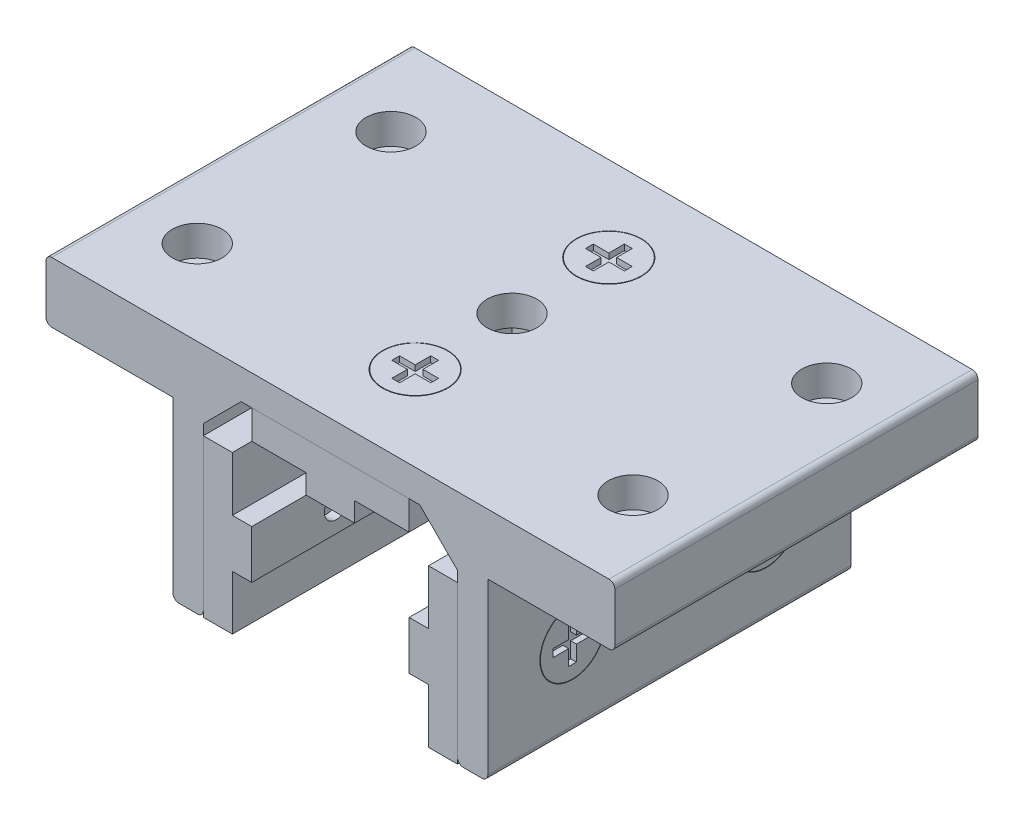
SolidWorks part; units mm, degrees
ref_plane "Front Plane" through (0, 0, 0) normal (0, 0, 1) x (1, 0, 0)
ref_plane "Top Plane" through (0, 0, 0) normal (0, 1, 0) x (1, 0, 0)
ref_plane "Right Plane" through (0, 0, 0) normal (1, 0, 0) x (0, 0, -1)
sketch "Sketch1" plane through (0, 0, 0) normal (0, 0, 1) x (1, 0, 0)
  line L0 (0, -15.4686) -> (0, 15.4686) construction
  line L1 (-20.6375, 0) -> (20.6375, 0) construction
  line L3 (-20.6375, -15.475) -> (-16.6687, -15.475) construction
  line L4 (-16.6687, -15.475) -> (-16.6687, 6.5389) construction
  line L5 (-16.6687, 6.5389) -> (-11.7078, 11.4998) construction
  line L6 (-11.7078, 11.4998) -> (11.7078, 11.4998) construction
  line L7 (11.7078, 11.4998) -> (16.6687, 6.5389) construction
  line L8 (16.6687, 6.5389) -> (16.6688, -15.4749) construction
  line L9 (16.6688, -15.4749) -> (20.6375, -15.475) construction
  line L10 (20.6375, -15.475) -> (20.6375, 7.5311) construction
  line L11 (20.6375, 7.5311) -> (-20.6375, 7.5311) construction
  line L14 (-16.6687, 5.1498) -> (-12.8588, 5.1498) construction
  line L15 (-12.8588, 5.1498) -> (-12.8587, -1.9876) construction
  line L16 (-12.8587, -1.9876) -> (-10.3187, -1.9876) construction
  line L17 (-10.3187, -1.9876) -> (-10.3187, -8.3376) construction
  line L18 (-10.3187, -8.3376) -> (-12.8587, -8.3376) construction
  line L19 (-12.8587, -8.3376) -> (-12.8587, -15.475) construction
  line L20 (-12.8587, -15.475) -> (-16.6687, -15.475) construction
  line L21 (-12.8587, -1.9876) -> (-12.8587, -8.3376) construction
  line L22 (-10.3187, -5.1626) -> (-16.6687, -5.1626) construction
  line L23 (-16.6687, -5.1626) -> (20.6375, -5.1626) construction
  line L24 (-37.2999, 15.4686) -> (37.2999, 15.4686) construction
  line L25 (-37.2999, 15.4686) -> (-37.2999, 7.5311) construction
  line L26 (-37.2999, 7.5311) -> (-20.6375, 7.5311) construction
  line L27 (-20.6375, 7.5311) -> (-20.6375, -15.475) construction
  line L28 (37.2999, 15.4686) -> (37.2999, 7.5311) construction
  line L29 (37.2999, 7.5311) -> (20.6375, 7.5311) construction
  point P4 (0, 0)
  point P7 (0, 0)
  point P30 (0, 11.4998)
  point P31 (0, 4.3561)
  dimension "Length (B)" = 30.9372
  dimension "Length1" = 41.275
  dimension "D1" = 3.9688
  dimension "Chamfer" = 4.9609
  dimension "D2" = 45
  dimension "Pad Width" = 20.6248
  dimension "Pad Height" = 6.35
  dimension "Pad Thickness" = 3.81
  dimension "Pad Rail" = 6.35
  dimension "Countersink Depth" = 3.175
  dimension "Inner Height" = 26.9748
  dimension "Length (A)" = 74.5998
  dimension "Mounting Hole Depth" = 7.9375
  dimension "D4" = 3.9688
sketch "Sketch2" plane through (0, 0, 0) normal (1, 0, 0) x (0, 0, -1)
  line L0 (-23.8125, 0) -> (23.8125, 0) construction
  line L1 (-23.8125, 7.5311) -> (23.8125, 7.5311) construction
  line L2 (-23.8125, 15.4686) -> (23.8125, 15.4686) construction
  line L3 (-23.8125, 15.4686) -> (-23.8125, -15.4686) construction
  line L4 (-23.8125, -15.4686) -> (23.8125, -15.4686) construction
  line L5 (23.8125, 15.4686) -> (23.8125, -15.4686) construction
  line L7 (0, 15.4686) -> (0, 7.5311) construction
  line L8 (-12.7, 11.4999) -> (12.7, 11.4999) construction
  line L9 (-23.8125, -5.1626) -> (23.8125, -5.1625) construction
  line L10 (-13.2105, -7.7153) -> (-12.1895, -7.7153) construction
  line L11 (-13.2105, -7.7153) -> (-13.2105, -2.6099) construction
  line L12 (-13.2105, -2.6099) -> (-12.1895, -2.6099) construction
  line L13 (-12.1895, -7.7153) -> (-12.1895, -2.6099) construction
  line L14 (-12.7, -2.6098) -> (-12.7, -7.7153) construction
  line L15 (-13.2105, -5.1626) -> (-12.1895, -5.1626) construction
  line L16 (-15.2527, -4.652) -> (-10.1473, -4.652) construction
  line L17 (-15.2527, -4.652) -> (-15.2527, -5.6731) construction
  line L18 (-15.2527, -5.6731) -> (-10.1473, -5.6731) construction
  line L19 (-10.1473, -4.652) -> (-10.1473, -5.6731) construction
  line L20 (-12.7, -5.6731) -> (-12.7, -4.652) construction
  line L21 (-15.2527, -5.1626) -> (-10.1473, -5.1626) construction
  line L22 (12.7, -2.6098) -> (-12.7, -2.6098) construction
  line L23 (0, -5.1626) -> (0, -2.6098) construction
  circle A0 centre (-12.7, 11.4999) radius 3.2639 construction
  circle A1 centre (12.7, 11.4999) radius 3.2639 construction
  circle A2 centre (0, -5.1626) radius 3.2639 construction
  circle A3 centre (-12.7, -5.1626) radius 2.5527 construction
  circle A4 centre (12.7, -5.1626) radius 2.5527 construction
  circle A5 centre (12.7, -5.1626) radius 1.5875
  circle A6 centre (-12.7, -5.1626) radius 1.5875
  point P12 (0, 7.5311)
  point P19 (0, 11.4998)
  point P22 (0, -5.1626)
  point P42 (0, -5.1626)
  dimension "Mounting Hole Diameter" = 6.5278
  dimension "Hole Diameter 2" = 6.5278
  dimension "D1" = 5.1054
  dimension "Pilot Hole" = 3.175
  dimension "Length" = 47.625
  dimension "Mounting Hole Spacing" = 25.4
  dimension "D2" = 1.0211
sketch "Sketch3" plane through (0, 0, 0) normal (0, 1, 0) x (1, 0, 0)
  line L0 (0, -23.8125) -> (0, 23.8125) construction
  line L1 (0, 12.7) -> (0, -12.7) construction
  line L5 (0, -23.8125) -> (0, 23.8125) construction
  line L7 (-28.575, 12.7) -> (28.575, 12.7) construction
  line L8 (-28.575, 12.7) -> (-28.575, -12.7) construction
  circle A0 centre (0, 12.7) radius 2.5527 construction
  circle A1 centre (0, -12.7) radius 2.5527 construction
  circle A2 centre (0, 0) radius 3.2639 construction
  circle A3 centre (0, 12.7) radius 4.2164 construction
  circle A4 centre (0, -12.7) radius 4.2164 construction
  circle A5 centre (-28.575, 12.7) radius 3.2639 construction
  circle A6 centre (28.575, 12.7) radius 3.2639 construction
  circle A7 centre (28.575, -12.7) radius 3.2639 construction
  circle A8 centre (-28.575, -12.7) radius 3.2639 construction
  dimension "D1" = 6.5278
  dimension "D2" = 5.1054
  dimension "Countersink Diameter" = 8.4328
  dimension "Hole Spacing2" = 57.15
ref_plane "Plane1" through (0, 0, 12.7) normal (0, 0, 1) x (1, 0, 0)
sketch "Sketch11" plane through (0, 0, 12.7) normal (0, 0, 1) x (1, 0, 0)
  line L0 (-16.6687, -5.1626) -> (-20.6375, -5.1626) construction
  line L2 (-20.6375, -0.9462) -> (-20.6375, -9.379) construction
  line L3 (-20.6375, -0.9462) -> (-19.1243, -2.7496) construction
  line L4 (-19.1243, -2.7496) -> (-19.1243, -7.5756) construction
  line L5 (-19.1243, -7.5756) -> (-20.6375, -9.379) construction
  line L6 (-19.1243, -2.7496) -> (-11.5887, -2.7496) construction
  line L7 (-11.5887, -2.7496) -> (-11.5887, -1.9876) construction
  line L8 (-12.8587, -1.9876) -> (-10.3187, -1.9876) construction
  line L9 (-20.6375, 7.5311) -> (-20.6375, -15.475) construction
  point P7 (-19.8809, -1.8479)
  dimension "D1" = 8.4328
  dimension "D2" = 100
  dimension "D3" = 4.826
sketch "Sketch4" plane through (0, 0, 0) normal (0, 0, 1) x (1, 0, 0)
  line L0 (-20.6375, -15.475) -> (-16.6687, -15.475) construction
  line L5 (20.6375, -15.475) -> (20.6375, 7.5311) construction
  line L6 (16.6688, -15.4749) -> (20.6375, -15.475) construction
  line L7 (16.6687, 6.5389) -> (16.6688, -15.4749) construction
  line L8 (11.7078, 11.4998) -> (16.6687, 6.5389) construction
  line L9 (-11.7078, 11.4998) -> (11.7078, 11.4998) construction
  line L10 (-16.6687, 6.5389) -> (-11.7078, 11.4998) construction
  line L11 (-16.6687, -15.475) -> (-16.6687, 6.5389) construction
  line L12 (-20.6375, -15.475) -> (-16.6687, -15.475)
  line L17 (20.6375, -15.475) -> (20.6375, 7.5311)
  line L18 (16.6688, -15.4749) -> (20.6375, -15.475)
  line L19 (16.6687, 6.5389) -> (16.6688, -15.4749)
  line L20 (11.7078, 11.4998) -> (16.6687, 6.5389)
  line L21 (-11.7078, 11.4998) -> (11.7078, 11.4998)
  line L22 (-16.6687, 6.5389) -> (-11.7078, 11.4998)
  line L23 (-16.6687, -15.475) -> (-16.6687, 6.5389)
  line L24 (-20.6375, -15.475) -> (-20.6375, 7.5311)
  line L25 (-20.6375, 7.5311) -> (-37.2999, 7.5311)
  line L26 (-37.2999, 7.5311) -> (-37.2999, 15.4686)
  line L27 (-37.2999, 15.4686) -> (37.2999, 15.4686)
  line L28 (37.2999, 15.4686) -> (37.2999, 7.5311)
  line L29 (37.2999, 7.5311) -> (20.6375, 7.5311)
extrude "Boss-Extrude1" add sketch "Sketch4" along normal up to vertex (23.8125 mm away) and the other way up to vertex (23.8125 mm away) up to point (0, -15.4686, 23.8125) other way up to point (0, 0, -23.8125)
sketch "Sketch5" plane through (0, 0, 0) normal (0, 0, 1) x (1, 0, 0)
  line L0 (-16.6687, 5.1498) -> (-16.6687, -15.475)
  line L1 (-16.6687, -15.475) -> (-12.8587, -15.475)
  line L2 (-12.8587, -15.475) -> (-12.8587, -8.3376)
  line L3 (-12.8587, -8.3376) -> (-10.3187, -8.3376)
  line L4 (-10.3187, -8.3376) -> (-10.3187, -1.9876)
  line L5 (-10.3187, -1.9876) -> (-12.8587, -1.9876)
  line L6 (-12.8587, -1.9876) -> (-12.8588, 5.1498)
  line L7 (-12.8588, 5.1498) -> (-16.6687, 5.1498)
extrude "Boss-Extrude2" add sketch "Sketch5" along normal up to surface and the other way up to surface from offset 1.7272 separate body
sketch "Sketch6" plane through (0, 0, 0) normal (1, 0, 0) x (0, 0, -1)
  circle A0 centre (-12.7, -5.1626) radius 2.5527 construction
  circle A1 centre (0, -5.1626) radius 3.2639 construction
  circle A2 centre (12.7, -5.1626) radius 2.5527 construction
  circle A5 centre (-12.7, -5.1626) radius 2.5527
  circle A6 centre (0, -5.1626) radius 3.2639
  circle A7 centre (12.7, -5.1626) radius 2.5527
extrude "Cut-Extrude1" cut sketch "Sketch6" against normal through all both and the other way through all
sketch "Sketch7" plane through (0, 0, 0) normal (1, 0, 0) x (0, 0, -1)
  line L1 (-3.2639, -8.4265) -> (3.2639, -8.4265)
  line L2 (-3.2639, -8.4265) -> (-3.2639, -1.8986)
  line L3 (-3.2639, -1.8986) -> (3.2639, -1.8986)
  line L4 (3.2639, -8.4265) -> (3.2639, -1.8986)
  line L5 (0, -1.8986) -> (0, -8.4265) construction
  line L6 (-3.2639, -5.1626) -> (3.2639, -5.1626) construction
  circle A0 centre (-12.7, -5.1626) radius 1.5875 construction
  circle A1 centre (-12.7, -5.1626) radius 1.5875
  circle A2 centre (12.7, -5.1626) radius 1.5875 construction
  circle A3 centre (12.7, -5.1626) radius 1.5875
  circle A4 centre (0, -5.1626) radius 3.2639 construction
  point P6 (0, -5.1626)
extrude "Cut-Extrude2" cut sketch "Sketch7" against normal through all
sketch "Sketch8" plane through (0, 15.4686, 0) normal (0, 1, 0) x (1, 0, 0)
  circle A0 centre (0, 12.7) radius 2.5527 construction
  circle A1 centre (0, -12.7) radius 2.5527 construction
  circle A2 centre (0, 12.7) radius 2.5527
  circle A3 centre (0, -12.7) radius 2.5527
  circle A4 centre (28.575, -12.7) radius 3.2639 construction
  circle A5 centre (28.575, 12.7) radius 3.2639 construction
  circle A6 centre (0, 0) radius 3.2639 construction
  circle A7 centre (-28.575, -12.7) radius 3.2639 construction
  circle A8 centre (-28.575, 12.7) radius 3.2639 construction
  circle A9 centre (28.575, -12.7) radius 3.2639
  circle A10 centre (28.575, 12.7) radius 3.2639
  circle A11 centre (0, 0) radius 3.2639
  circle A12 centre (-28.575, -12.7) radius 3.2639
  circle A13 centre (-28.575, 12.7) radius 3.2639
extrude "Cut-Extrude3" cut sketch "Sketch8" against normal up to vertex (3.9688 mm away) up to point (0, 11.4998, 0)
chamfer "Chamfer1" distance 1.7272 angle 45 6 edges at (20.6375, -7.7153, 12.7) (20.6375, -7.7153, -12.7) (0, 15.4686, 15.2527) (0, 15.4686, -10.1473) (-20.6375, -2.6098, -12.7) (-20.6375, -2.6098, 12.7)
sketch "Sketch12" plane through (0, 0, 12.7) normal (0, 0, 1) x (1, 0, 0)
  line L0 (-20.6375, -0.9462) -> (-20.6375, -5.1626)
  line L1 (-20.6375, -5.1626) -> (-11.5887, -5.1626)
  line L2 (-11.5887, -5.1626) -> (-11.5887, -2.7496)
  line L3 (-11.5887, -2.7496) -> (-19.1243, -2.7496)
  line L4 (-19.1243, -2.7496) -> (-20.6375, -0.9462)
revolve "Revolve1" add sketch "Sketch12" angle 360 about L1
sketch "Sketch13" plane through (-20.6375, 0, 0) normal (-1, 0, 0) x (0, 0, 1)
  line L0 (13.2105, -7.7153) -> (12.1895, -7.7153) construction
  line L1 (13.2105, -7.7153) -> (13.2105, -2.6099) construction
  line L2 (13.2105, -2.6099) -> (12.1895, -2.6099) construction
  line L3 (12.1895, -7.7153) -> (12.1895, -2.6099) construction
  line L4 (13.2105, -7.7153) -> (12.1895, -7.7153)
  line L5 (13.2105, -7.7153) -> (13.2105, -5.6731)
  line L6 (13.2105, -2.6099) -> (12.1895, -2.6099)
  line L7 (12.1895, -7.7153) -> (12.1895, -5.6731)
  line L8 (15.2527, -4.652) -> (15.2527, -5.6731) construction
  line L9 (15.2527, -5.6731) -> (10.1473, -5.6731) construction
  line L10 (10.1473, -4.652) -> (10.1473, -5.6731) construction
  line L11 (15.2527, -4.652) -> (10.1473, -4.652) construction
  line L12 (15.2527, -4.652) -> (15.2527, -5.6731)
  line L13 (15.2527, -5.6731) -> (13.2105, -5.6731)
  line L14 (10.1473, -4.652) -> (10.1473, -5.6731)
  line L15 (15.2527, -4.652) -> (13.2105, -4.652)
  line L16 (12.1895, -4.652) -> (10.1473, -4.652)
  line L17 (12.1895, -4.652) -> (12.1895, -2.6099)
  line L18 (12.1895, -5.6731) -> (10.1473, -5.6731)
  line L19 (13.2105, -4.652) -> (13.2105, -2.6099)
extrude "Cut-Extrude5" cut sketch "Sketch13" against normal up to vertex (0.7566 mm away) up to point (-19.8809, -1.8479, 12.7)
pattern_linear "LPattern1" count 2 spacing 25.4 along (0, 0, -1) of bodies 111
pattern_circular "CirPattern1" count 3 over 180 about axis through (0, -5.1626, 0) along (0, 0, 1) of bodies 107 111 112
fillet "Fillet1" radius 0.762 8 edges at (20.6375, -15.475, 0) (16.6688, -15.4749, 0) (-16.6687, -15.475, 0) (37.2999, 7.5311, 0) (37.2999, 15.4686, 0) (-37.2999, 15.4686, 0) (-37.2999, 7.5311, 0) (-20.6375, -15.475, 0)
equation "\"D1@Sketch1\" = \"Mounting Hole Depth@Sketch1\" / 2"
equation "\"D1@Sketch3\"=\"Hole Diameter 2@Sketch2\""
equation "\"D2@Sketch3\"=\"D1@Sketch2\""
equation "\"D2@Sketch2\"=\"D1@Sketch2\"*.2"
equation "\"D1@Sketch11\"=\"Countersink Diameter@Sketch3\""
equation "\"D3@LPattern1\"=\"Mounting Hole Spacing@Sketch2\""
equation "\"Chamfer@Sketch1\"=\"Mounting Hole Depth@Sketch1\"*.625"
equation "\"D4@Sketch1\"=\"Mounting Hole Depth@Sketch1\"/2"
